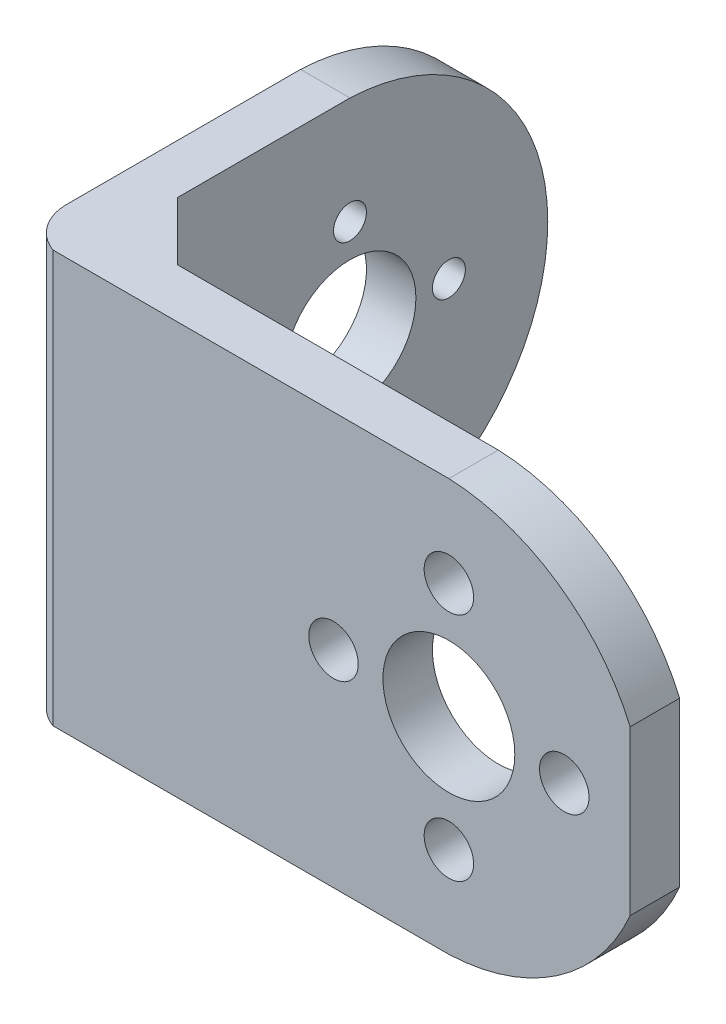
SolidWorks part; units mm, degrees
material "1060 Alloy"
ref_plane "Front Plane" through (0, 0, 0) normal (0, 0, 1) x (1, 0, 0)
ref_plane "Top Plane" through (0, 0, 0) normal (0, 1, 0) x (1, 0, 0)
ref_plane "Right Plane" through (0, 0, 0) normal (1, 0, 0) x (0, 0, -1)
sketch "Sketch1" plane through (0, 0, 0) normal (0, 1, 0) x (1, 0, 0)
  line L0 (0.9798, -1) -> (36, -1)
  line L1 (36, -1) -> (36, 2)
  line L2 (36, 2) -> (2.9676, 2)
  line L3 (-1, 2) -> (-1, 1.6591)
  line L4 (-1, 1.6591) -> (-1, 28)
  line L5 (-1, 28) -> (2, 28)
  line L6 (2, 28) -> (2, 2.9676)
  arc A0 (-1, 2) -> (3.0294, -1) centre (2.0046, 1.8295) ccw
  arc A1 (2, 2.9676) -> (3.0387, 2) centre (3.0031, 3.0031) ccw
  dimension "D1" = 3
  dimension "D2" = 3
extrude "Boss-Extrude1" add sketch "Sketch1" along normal blind 25 contours A1 L6 L5 L4 L3 A0 L0 L1 L2
sketch "Sketch2" plane through (-1, 0, 0) normal (-1, 0, 0) x (0, 0, 1)
  line L0 (-28, 12.5) -> (-16, 12.5) construction
  line L1 (-28, 25) -> (-28, 0) construction
  line L2 (-1.6591, 0) -> (-28, 0) construction
  line L3 (-1.6591, 25) -> (-28, 25) construction
  line L4 (-16, 25) -> (-28, 25)
  line L5 (-28, 25) -> (-28, 12.5)
  line L6 (-28, 12.5) -> (-28, 0)
  line L7 (-28, 0) -> (-16, 0)
  arc A0 (-16, 0) -> (-16, 25) centre (-15.4896, 12.5) cw
  line M3 (-28, 0) -> (-1.6591, 0)
  line M5 (-1.6591, 25) -> (-28, 25)
  line M6 (-28, 25) -> (-28, 0)
  dimension "D1" = 12
extrude "Cut-Extrude1" cut sketch "Sketch2" against normal blind 25 contours A0 M6 M5 | A0 M3 M6
sketch "Sketch4" plane through (0, 0, 1) normal (0, 0, 1) x (1, 0, 0)
  line L0 (36, 12.5) -> (25, 12.5) construction
  line L1 (36, 25) -> (36, 0) construction
  line L2 (0.9798, 0) -> (36, 0) construction
  line L3 (0.9798, 25) -> (36, 25) construction
  line L4 (25, 25) -> (36, 25)
  line L5 (36, 25) -> (36, 12.5)
  line L6 (36, 12.5) -> (36, 0)
  line L7 (36, 0) -> (25, 0)
  line L8 (25, 12.5) -> (25, 19.5) construction
  circle A0 centre (25, 12.5) radius 4
  arc A1 (25, 0) -> (25, 25) centre (24.5166, 12.5) ccw
  circle A2 centre (25, 19.5) radius 1.5
  circle A3 centre (32, 12.5) radius 1.5
  circle A4 centre (25, 5.5) radius 1.5
  circle A5 centre (18, 12.5) radius 1.5
  point P27 (25, 12.5)
  line M1 (0.9798, 0) -> (36, 0)
  line M2 (36, 0) -> (36, 25)
  line M3 (36, 25) -> (0.9798, 25)
  dimension "D1" = 3
  dimension "D2" = 4
extrude "Cut-Extrude2" cut sketch "Sketch4" against normal blind 25 contours A1 L5 M3 | A1 M1 M2
sketch "Sketch5" plane through (0, 0, 1) normal (0, 0, 1) x (1, 0, 0)
  line L0 (36, 12.5) -> (25, 12.5) construction
  line L1 (36, 17.4614) -> (36, 7.5386) construction
  line L2 (25, 12.5) -> (25, 19.5) construction
  circle A0 centre (25, 12.5) radius 4
  circle A5 centre (25, 19.5) radius 1.5
  circle A6 centre (32, 12.5) radius 1.5
  circle A7 centre (25, 5.5) radius 1.5
  circle A8 centre (18, 12.5) radius 1.5
  point P16 (25, 12.5)
  point P17 (25, 12.5)
  dimension "D1" = 7
  dimension "D2" = 4
extrude "Cut-Extrude3" cut sketch "Sketch5" against normal blind 25
sketch "Sketch6" plane through (-1, 0, 0) normal (-1, 0, 0) x (0, 0, 1)
  line L0 (-28, 12.5) -> (-16, 12.5) construction
  line L1 (-16, 12.5) -> (-16, 5.5) construction
  arc A0 (-16, 25) -> (-16, 0) centre (-15.4896, 12.5) ccw construction
  circle A1 centre (-16, 12.5) radius 4
  circle A6 centre (-16, 12.5) radius 6 construction
  circle A7 centre (-16, 18.5) radius 1
  circle A10 centre (-10, 12.5) radius 1
  circle A11 centre (-16, 6.5) radius 1
  circle A12 centre (-22, 12.5) radius 1
  point P18 (-16, 12.5)
  point P25 (-16, 12.5)
  dimension "D1" = 7
  dimension "D2" = 4
  dimension "D3" = 12
  dimension "D4" = 2
extrude "Cut-Extrude4" cut sketch "Sketch6" against normal blind 25
sketch "Sketch7" plane through (0, 25, 0) normal (0, 1, 0) x (1, 0, 0)
  line L0 (0.9982, 6.5452) -> (6.4564, 1.087)
  line L1 (0.9982, 1.087) -> (0.9982, 6.5452)
  line L2 (0.9982, 1.087) -> (6.4564, 1.087)
  line L3 (0.9798, -1) -> (25, -1) construction
  line L4 (-1, 1.6591) -> (-1, 16) construction
extrude "Boss-Extrude2" add sketch "Sketch7" against normal up to surface (25 mm away) up to face at (6.9274, 0, -4.7643)
